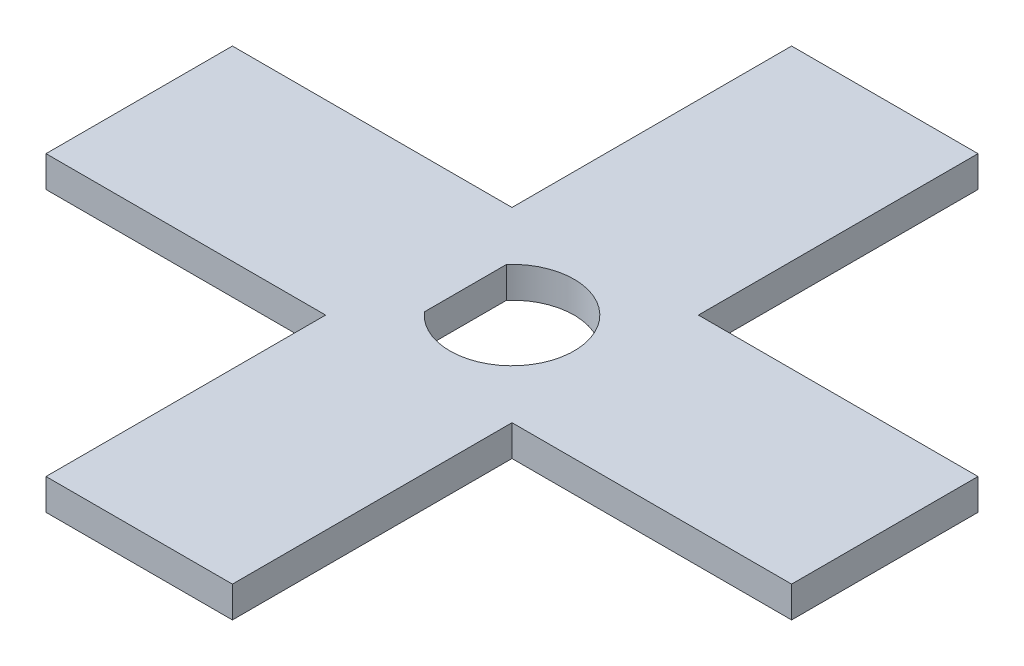
SolidWorks part; units mm, degrees
ref_plane "Front Plane" through (0, 0, 0) normal (0, 0, 1) x (1, 0, 0)
ref_plane "Top Plane" through (0, 0, 0) normal (0, 1, 0) x (1, 0, 0)
ref_plane "Right Plane" through (0, 0, 0) normal (1, 0, 0) x (0, 0, -1)
sketch "Sketch1" plane through (0, 0, 0) normal (0, 1, 0) x (1, 0, 0)
  line L0 (-6, 6) -> (-6, 24)
  line L1 (-6, 24) -> (6, 24)
  line L2 (6, 24) -> (6, 6)
  line L3 (6, 6) -> (24, 6)
  line L4 (24, 6) -> (24, -6)
  line L5 (24, -6) -> (6, -6)
  line L6 (6, -6) -> (6, -24)
  line L7 (6, -24) -> (-6, -24)
  line L8 (-6, -24) -> (-6, -6)
  line L9 (-6, -6) -> (-24, -6)
  line L10 (-24, -6) -> (-24, 6)
  line L11 (-24, 6) -> (-6, 6)
  point P0 (-24, 0)
  point P1 (0, 24)
  point P9 (0, 0)
  dimension "D2" = 12
  dimension "D3" = 18
extrude "Boss-Extrude1" add sketch "Sketch1" along normal blind 2 contours L5 L6 L7 L8 L9 L10 L11 L0 L1 L2 L3 L4
sketch "Sketch2" plane through (0, 0, 0) normal (0, 1, 0) x (1, 0, 0)
  line L4 (-3, -2.6458) -> (-3, 2.6458)
  arc A0 (-3, -2.6458) -> (-3, 2.6458) centre (0, 0) ccw
  point P3 (-5.5732, 0)
  dimension "D1" = 8
  dimension "D2" = 3
extrude "Cut-Extrude2" cut sketch "Sketch2" along normal through all
